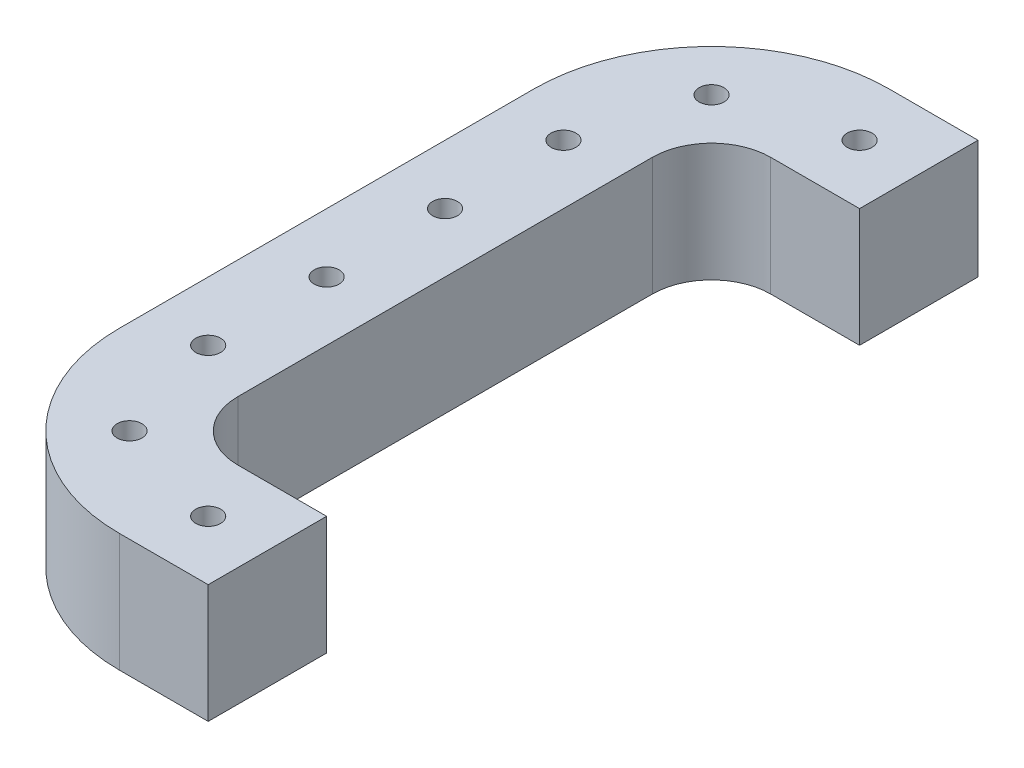
SolidWorks part; units mm, degrees
material "Custom Plastic"
ref_plane "Front Plane" through (0, 0, 0) normal (0, 0, 1) x (1, 0, 0)
ref_plane "Top Plane" through (0, 0, 0) normal (0, 1, 0) x (1, 0, 0)
ref_plane "Right Plane" through (0, 0, 0) normal (1, 0, 0) x (0, 0, -1)
sketch "Sketch1" plane through (0, 0, 0) normal (0, 1, 0) x (1, 0, 0)
  line L0 (0, 0) -> (0, 15) construction
  line L1 (20, 35) -> (35, 35) construction
  line L2 (10, 0) -> (10, 15)
  line L3 (20, 25) -> (35, 25)
  line L4 (-10, 0) -> (-10, 15)
  line L5 (20, 45) -> (35, 45)
  line L6 (10, 0) -> (-10, 0)
  line L7 (35, 25) -> (35, 45)
  arc A0 (0, 15) -> (20, 35) centre (20, 15) cw construction
  arc A1 (10, 15) -> (20, 25) centre (20, 15) cw
  arc A2 (-10, 15) -> (20, 45) centre (20, 15) cw
  point P6 (0, 35)
  dimension "D2" = 20
  dimension "D1" = 35
  dimension "D3" = 10
  dimension "D4" = 10
extrude "Boss-Extrude1" add sketch "Sketch1" along normal mid plane 20
sketch "Sketch3" plane through (0, 10, 0) normal (0, 1, 0) x (1, 0, 0)
  line L0 (-10, 15) -> (-10, 0) construction
  line L1 (10, 0) -> (-10, 0)
  line L2 (10, 0) -> (10, -20)
  line L3 (10, -20) -> (-10, -20)
  line L4 (-10, 0) -> (-10, -20)
  dimension "D1" = 20
extrude "Boss-Extrude2" add sketch "Sketch3" against normal up to surface (20 mm away) up to face at (12.7145, -10, -22.2855)
sketch "Sketch2" plane through (0, 10, 0) normal (0, 1, 0) x (1, 0, 0)
  line L0 (12.9289, 22.0711) -> (-1.2132, 36.2132) construction
  line L1 (0, 0) -> (0, 35) construction
  line L3 (0, 0) -> (0, -20) construction
  line L4 (-10, -20) -> (10, -20) construction
  arc A0 (20, 25) -> (10, 15) centre (20, 15) ccw construction
  arc A1 (20, 45) -> (-10, 15) centre (20, 15) ccw construction
  circle A2 centre (5.8579, 29.1421) radius 2.1
  circle A3 centre (0, 10) radius 2.1
  circle A5 centre (25, 35) radius 2.1
  circle A6 centre (0, -10) radius 2.1
  dimension "D1" = 4.2
  dimension "D2" = 10
  dimension "D3" = 20
  dimension "D4" = 4.2
extrude "Cut-Extrude1" cut sketch "Sketch2" against normal through all
mirror "Mirror1" about plane through (10, -38.2843, 20) normal (0, 0, 1) of bodies 102
